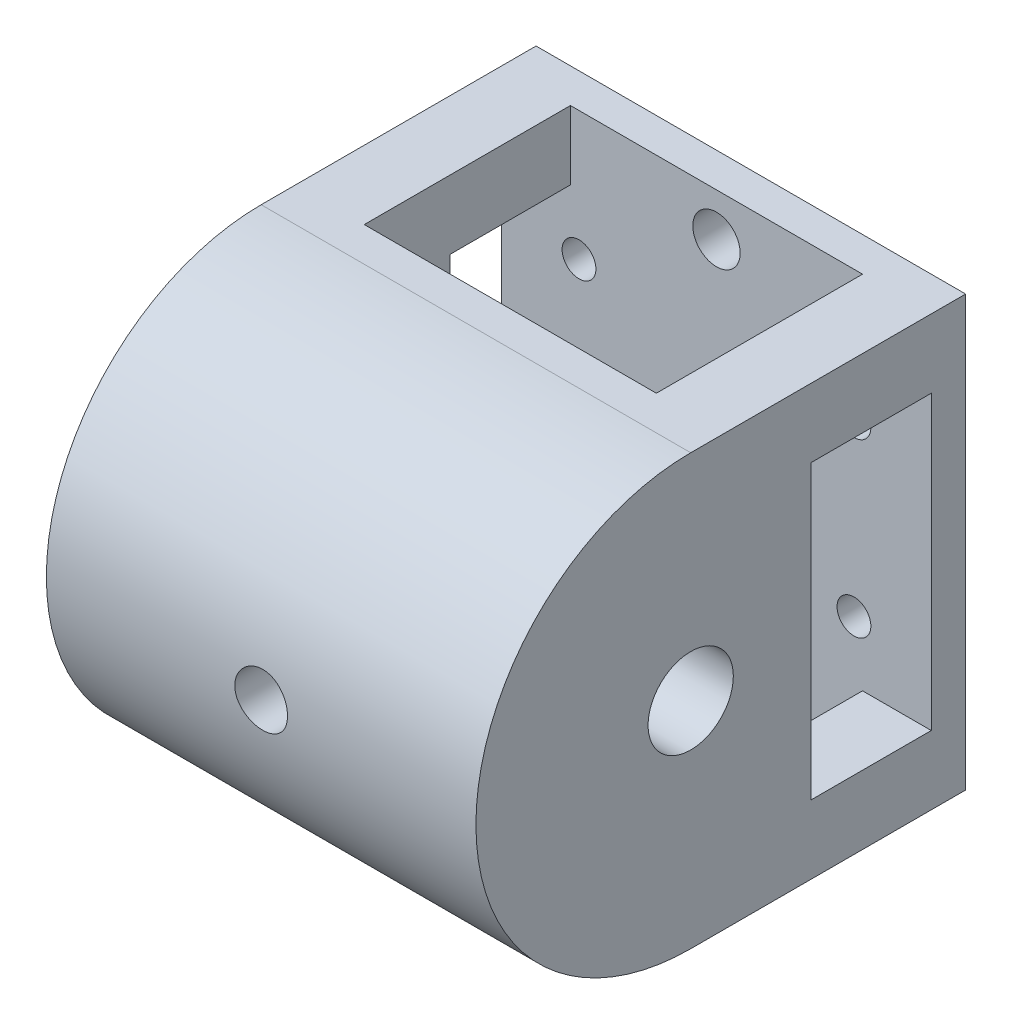
SolidWorks part; units mm, degrees
material "PLA"
ref_plane "Front Plane" through (0, 0, 0) normal (0, 0, 1) x (1, 0, 0)
ref_plane "Top Plane" through (0, 0, 0) normal (0, 1, 0) x (1, 0, 0)
ref_plane "Right Plane" through (0, 0, 0) normal (1, 0, 0) x (0, 0, -1)
sketch "Sketch1" plane through (0, 0, 0) normal (1, 0, 0) x (0, 0, -1)
  line L0 (0, 15.875) -> (20.32, 15.875)
  line L1 (20.32, 15.875) -> (20.32, -15.875)
  line L2 (20.32, -15.875) -> (0, -15.875)
  circle A0 centre (0, 0) radius 15.875
  circle A1 centre (0, 0) radius 3.15
  dimension "D1" = 31.75
  dimension "D3" = 6.3
  dimension "D2" = 20.32
extrude "Boss-Extrude1" add sketch "Sketch1" along normal blind 31.75 contours A0 | A0 L2 L1 L0
sketch "Sketch2" plane through (0, 0, -20.32) normal (0, 0, -1) x (-1, 0, 0)
  line L0 (-15.875, 0) -> (-15.875, 6.1274) construction
  line L1 (-15.875, 0) -> (-7.897, 0) construction
  line L4 (0, -15.875) -> (0, 15.875)
  line L5 (0, 15.875) -> (-31.75, 15.875)
  line L6 (-31.75, 15.875) -> (-31.75, -15.875)
  line L7 (-31.75, -15.875) -> (0, -15.875)
  line L8 (0, -15.875) -> (0, 15.875)
  line L9 (0, 15.875) -> (-31.75, 15.875)
  line L10 (-31.75, 15.875) -> (-31.75, -15.875)
  line L11 (-31.75, -15.875) -> (0, -15.875)
  circle A0 centre (-15.875, 0) radius 15.875 construction
  circle A1 centre (-26.035, 6.35) radius 1.25
  circle A2 centre (-5.715, 6.35) radius 1.25
  circle A3 centre (-5.715, -6.35) radius 1.25
  circle A4 centre (-26.035, -6.35) radius 1.25
  point P2 (-15.875, 0)
  point P6 (-15.875, 15.875)
  dimension "D2" = 31.75
  dimension "D3" = 2.5
  dimension "D4" = 12.7
  dimension "D5" = 20.32
  dimension "D1" = 0
sketch "Sketch4" plane through (0, 0, 0) normal (-1, 0, 0) x (0, 0, 1)
  line L0 (-17.78, 15.875) -> (-17.78, -15.875)
  line L1 (-8.89, 15.875) -> (-8.89, -15.875)
  line L2 (0, 15.875) -> (-20.32, 15.875) construction
  line L3 (0, 15.875) -> (-20.32, 15.875)
  line L4 (-20.32, 15.875) -> (-20.32, -15.875)
  line L5 (-20.32, -15.875) -> (0, -15.875)
  line L6 (0, 15.875) -> (-20.32, 15.875)
  line L7 (-20.32, 15.875) -> (-20.32, -15.875)
  line L8 (-20.32, -15.875) -> (0, -15.875)
  line L9 (-8.89, 10.795) -> (-17.78, 10.795)
  line L10 (-17.78, -10.795) -> (-8.89, -10.795)
  arc A1 (0, -15.875) -> (0, 15.875) centre (0, 0) ccw
  arc A2 (0, -15.875) -> (0, 15.875) centre (0, 0) ccw
  dimension "D2" = 2.54
  dimension "D3" = 8.89
  dimension "D4" = 5.08
  dimension "D5" = 5.08
  dimension "D1" = 0
extrude "Cut-Extrude1" cut sketch "Sketch4" against normal through all contours L0 L10 L1 L9
extrude "Cut-Extrude2" cut sketch "Sketch2" against normal up to surface (2.54 mm away) contours A1 | A2 | A3 | A4 up to face at (15.875, 0, -17.78)
sketch "Sketch5" plane through (0, 15.875, 0) normal (0, 1, 0) x (1, 0, 0)
  line L0 (5.08, 17.78) -> (5.08, 8.89)
  line L1 (26.67, 8.89) -> (26.67, 17.78)
  line L4 (0, 17.78) -> (0, 8.89)
  line L5 (0, 8.89) -> (31.75, 8.89)
  line L6 (31.75, 8.89) -> (31.75, 17.78)
  line L7 (31.75, 17.78) -> (0, 17.78)
  line L8 (0, 17.78) -> (0, 8.89)
  line L9 (0, 8.89) -> (31.75, 8.89)
  line L10 (31.75, 8.89) -> (31.75, 17.78)
  line L11 (31.75, 17.78) -> (0, 17.78)
  dimension "D2" = 5.08
  dimension "D3" = 5.08
  dimension "D1" = 0
extrude "Cut-Extrude3" cut sketch "Sketch5" against normal through all contours L1 L11 L0 L9
sketch "Sketch6" plane through (0, 0, -20.32) normal (0, 0, -1) x (-1, 0, 0)
  line L0 (0, 0) -> (-5.8796, 0) construction
  line L4 (0, -15.875) -> (0, 15.875)
  line L5 (0, 15.875) -> (-31.75, 15.875)
  line L6 (-31.75, 15.875) -> (-31.75, -15.875)
  line L7 (-31.75, -15.875) -> (0, -15.875)
  line L8 (0, -15.875) -> (0, 15.875)
  line L9 (0, 15.875) -> (-31.75, 15.875)
  line L10 (-31.75, 15.875) -> (-31.75, -15.875)
  line L11 (-31.75, -15.875) -> (0, -15.875)
  circle A0 centre (-15.875, 12.7) radius 1.75
  circle A1 centre (-15.875, -12.7) radius 1.75
  point P6 (-15.875, 15.875)
  dimension "D1" = 3.5
  dimension "D2" = 12.7
  dimension "D3" = 0
extrude "Cut-Extrude4" cut sketch "Sketch6" against normal up to surface (2.54 mm away) contours A0 | A1 up to face at (26.035, -5.1, -17.78)
ref_plane "Plane1" through (0, 0, 50.8) normal (0, 0, 1) x (1, 0, 0)
sketch "Sketch7" plane through (0, 0, 50.8) normal (0, 0, 1) x (1, 0, 0)
  line L12 (0, -10.795) -> (5.08, -10.795)
  line L13 (5.08, -10.795) -> (5.08, -15.875)
  line L14 (5.08, -15.875) -> (26.67, -15.875)
  line L15 (26.67, -15.875) -> (26.67, -10.795)
  line L16 (26.67, -10.795) -> (31.75, -10.795)
  line L17 (31.75, -10.795) -> (31.75, 10.795)
  line L18 (31.75, 10.795) -> (26.67, 10.795)
  line L19 (26.67, 10.795) -> (26.67, 15.875)
  line L20 (26.67, 15.875) -> (5.08, 15.875)
  line L21 (5.08, 15.875) -> (5.08, 10.795)
  line L22 (5.08, 10.795) -> (0, 10.795)
  line L23 (0, 10.795) -> (0, -10.795)
  line L24 (0, -10.795) -> (5.08, -10.795)
  line L25 (5.08, -10.795) -> (5.08, -15.875)
  line L26 (5.08, -15.875) -> (26.67, -15.875)
  line L27 (26.67, -15.875) -> (26.67, -10.795)
  line L28 (26.67, -10.795) -> (31.75, -10.795)
  line L29 (31.75, -10.795) -> (31.75, 10.795)
  line L30 (31.75, 10.795) -> (26.67, 10.795)
  line L31 (26.67, 10.795) -> (26.67, 15.875)
  line L32 (26.67, 15.875) -> (5.08, 15.875)
  line L33 (5.08, 15.875) -> (5.08, 10.795)
  line L34 (5.08, 10.795) -> (0, 10.795)
  line L35 (0, 10.795) -> (0, -10.795)
  circle A0 centre (15.875, 0) radius 1.95
  dimension "D2" = 3.9
  dimension "D1" = 0
extrude "Cut-Extrude5" cut sketch "Sketch7" against normal up to surface (47.65 mm away) contours A0
sketch "Sketch8" plane through (0, 0, -8.89) normal (0, 0, -1) x (-1, 0, 0)
  line L0 (-26.67, 10.795) -> (-26.67, 9.525)
  line L1 (-26.67, 9.525) -> (-5.08, 9.525)
  line L2 (-5.08, 9.525) -> (-5.08, 10.795)
  line L3 (-31.75, 0) -> (-19.4562, 0) construction
  line L4 (-5.08, -9.525) -> (-5.08, -10.795)
  line L5 (-26.67, -10.795) -> (-26.67, -9.525)
  line L6 (-26.67, -9.525) -> (-5.08, -9.525)
  line L12 (0, 10.795) -> (-5.08, 10.795)
  line L13 (-5.08, 10.795) -> (-5.08, 15.875)
  line L14 (-5.08, 15.875) -> (-26.67, 15.875)
  line L15 (-26.67, 15.875) -> (-26.67, 10.795)
  line L16 (-26.67, 10.795) -> (-31.75, 10.795)
  line L17 (-31.75, 10.795) -> (-31.75, -10.795)
  line L18 (-31.75, -10.795) -> (-26.67, -10.795)
  line L19 (-26.67, -10.795) -> (-26.67, -15.875)
  line L20 (-26.67, -15.875) -> (-5.08, -15.875)
  line L21 (-5.08, -15.875) -> (-5.08, -10.795)
  line L22 (-5.08, -10.795) -> (0, -10.795)
  line L23 (0, -10.795) -> (0, 10.795)
  line L24 (0, 10.795) -> (-5.08, 10.795)
  line L25 (-5.08, 10.795) -> (-5.08, 15.875)
  line L26 (-5.08, 15.875) -> (-26.67, 15.875)
  line L27 (-26.67, 15.875) -> (-26.67, 10.795)
  line L28 (-26.67, 10.795) -> (-31.75, 10.795)
  line L29 (-31.75, 10.795) -> (-31.75, -10.795)
  line L30 (-31.75, -10.795) -> (-26.67, -10.795)
  line L31 (-26.67, -10.795) -> (-26.67, -15.875)
  line L32 (-26.67, -15.875) -> (-5.08, -15.875)
  line L33 (-5.08, -15.875) -> (-5.08, -10.795)
  line L34 (-5.08, -10.795) -> (0, -10.795)
  line L35 (0, -10.795) -> (0, 10.795)
  line M18 (-5.08, 10.795) -> (-5.08, 15.875)
  line M19 (-5.08, 15.875) -> (-26.67, 15.875)
  line M20 (-26.67, 15.875) -> (-26.67, 10.795)
  line M24 (-26.67, -10.795) -> (-26.67, -15.875)
  line M25 (-26.67, -15.875) -> (-5.08, -15.875)
  line M26 (-5.08, -15.875) -> (-5.08, -10.795)
  dimension "D2" = 6.35
  dimension "D1" = 0
extrude "Cut-Extrude6" cut sketch "Sketch8" against normal blind 6.35 contours L1 L2 L0 M18 M19 M20 | L6 L5 L4 M24 M25 M26
